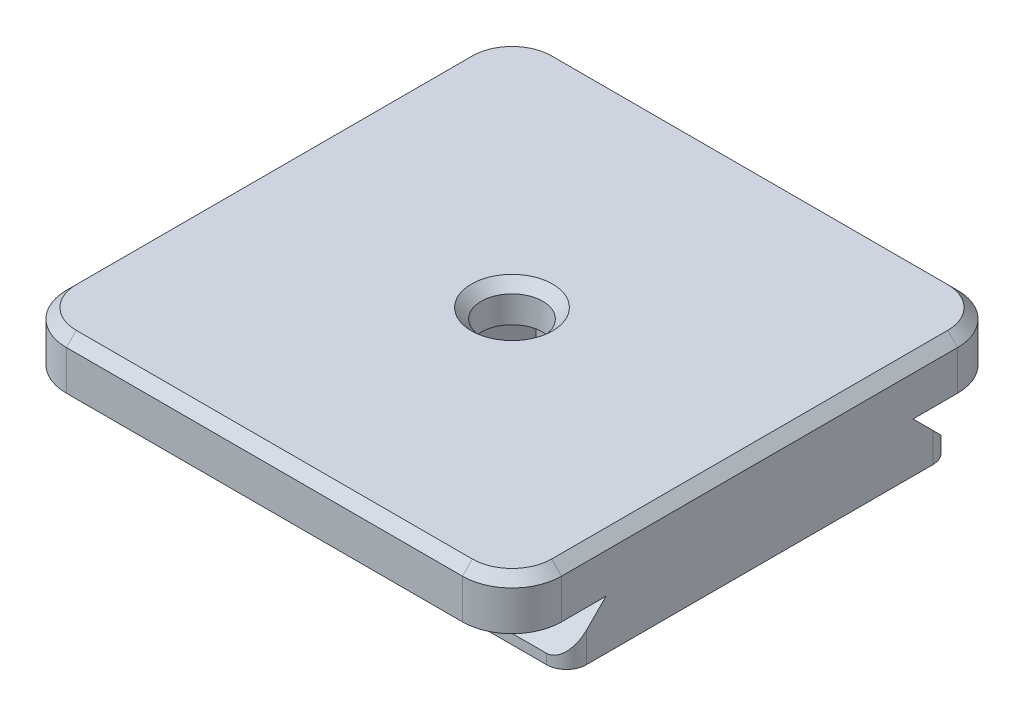
SolidWorks part; units mm, degrees
ref_plane "Front Plane" through (0, 0, 0) normal (0, 0, 1) x (1, 0, 0)
ref_plane "Top Plane" through (0, 0, 0) normal (0, 1, 0) x (1, 0, 0)
ref_plane "Right Plane" through (0, 0, 0) normal (1, 0, 0) x (0, 0, -1)
sketch "Sketch1" plane through (0, 0, 0) normal (0, 1, 0) x (1, 0, 0)
  line L1 (25, -25) -> (-25, -25)
  line L2 (25, -25) -> (25, 25)
  line L3 (25, 25) -> (-25, 25)
  line L4 (-25, -25) -> (-25, 25)
  line L5 (25, -25) -> (-25, 25) construction
  line L6 (25, 25) -> (-25, -25) construction
  point P0 (0, 0)
  dimension "D1" = 50
  dimension "D2" = 50
extrude "Boss-Extrude1" add sketch "Sketch1" along normal blind 10
sketch "Sketch4" plane through (0, 0, 0) normal (0, -1, 0) x (-1, 0, 0)
  line L0 (21, -7.2284) -> (21, -10.5)
  line L1 (-18.5, 13) -> (18.5, 13)
  line L2 (-21, 10.5) -> (-21, 7.2284)
  line L3 (-18.5, -13) -> (18.5, -13)
  line L4 (21, 10.5) -> (21, 7.2284)
  line L5 (-21, 13) -> (21, -13) construction
  line L6 (-21, -13) -> (21, 13) construction
  line L7 (-21, -7.2284) -> (-21, -10.5)
  arc A0 (19.5333, 5.3008) -> (19.5333, -5.3008) centre (21, 0) ccw
  arc A1 (-19.5333, -5.3008) -> (-19.5333, 5.3008) centre (-21, 0) ccw
  arc A2 (-21, -10.5) -> (-18.5, -13) centre (-18.5, -10.5) ccw
  arc A3 (-18.5, 13) -> (-21, 10.5) centre (-18.5, 10.5) ccw
  arc A4 (18.5, 13) -> (21, 10.5) centre (18.5, 10.5) cw
  arc A5 (18.5, -13) -> (21, -10.5) centre (18.5, -10.5) ccw
  arc A6 (-19.5333, -5.3008) -> (-21, -7.2284) centre (-19, -7.2284) ccw
  arc A7 (-21, 7.2284) -> (-19.5333, 5.3008) centre (-19, 7.2284) ccw
  arc A8 (19.5333, 5.3008) -> (21, 7.2284) centre (19, 7.2284) ccw
  arc A9 (19.5333, -5.3008) -> (21, -7.2284) centre (19, -7.2284) cw
  point P0 (0, 0)
  point P26 (-21, -5.5)
  point P33 (21, -5.5)
  dimension "D3" = 11
  dimension "D4" = 11
  dimension "D5" = 2.5
  dimension "D6" = 2
  dimension "D1" = 42
  dimension "D2" = 26
extrude "Cut-Extrude3" cut sketch "Sketch4" against normal blind 6.3
sketch "Sketch5" plane through (0, 6.3, 0) normal (0, -1, 0) x (-1, 0, 0)
  circle A0 centre (0, 0) radius 9
  circle A1 centre (0, 0) radius 3.1
  dimension "D1" = 18
  dimension "D2" = 6.2
extrude "Boss-Extrude2" add sketch "Sketch5" along normal blind 6
sketch "Sketch6" plane through (0, 0, 0) normal (0, -1, 0) x (1, 0, 0)
  line L0 (-25, -25) -> (-25, 25) construction
  circle A0 centre (-20, 0) radius 2.7
  circle A1 centre (20, 0) radius 2.7
  dimension "D1" = 5.4
  dimension "D2" = 40
  dimension "D3" = 5
extrude "Boss-Extrude3" add sketch "Sketch6" along normal blind 2.5
fillet "Fillet1" radius 0.5 2 edges at (20, -2.5, -2.7) (-20, -2.5, -2.7)
sketch "Sketch8" plane through (25, 0, 0) normal (1, 0, 0) x (0, 0, -1)
  line L0 (25, 10) -> (25, 0) construction
  line L16 (-25, 0) -> (-25, 5)
  line L17 (-25, 5) -> (-15.5, 5)
  line L18 (25, 0) -> (25, 5)
  line L19 (15.5, 5) -> (25, 5)
  line L20 (-25, 0) -> (25, 0) construction
  line L22 (-20.5, 0) -> (-15.5, 5)
  line L23 (20.5, 0) -> (15.5, 5)
  line L24 (-20.5, 0) -> (-25, 0)
  line L25 (20.5, 0) -> (25, 0)
  dimension "D1" = 9.5
  dimension "D2" = 45
extrude "Cut-Extrude4" cut sketch "Sketch8" against normal through all
fillet "Fillet2" radius 5 4 edges at (25, 7.5, -25) (-25, 7.5, -25) (-25, 7.5, 25) (25, 7.5, 25)
chamfer "Chamfer1" distance 1 angle 45 8 edges at (23.5355, 10, 23.5355) (0, 10, 25) (-23.5355, 10, 23.5355) (-25, 10, 0) (-23.5355, 10, -23.5355) (0, 10, -25) (23.5355, 10, -23.5355) (25, 10, 0)
chamfer "Chamfer2" distance 1 angle 90 2 edges at (0, 0, 20.5) (0, 0, -20.5)
fillet "Fillet3" radius 2 4 edges at (25, 0.5, -19.5) (25, 0.5, 19.5) (-25, 0.5, 19.5) (-25, 0.5, -19.5)
sketch "Sketch9" plane through (0, 6.3, 0) normal (0, -1, 0) x (-1, 0, 0)
  circle A0 centre (0, 0) radius 3.1
extrude "Cut-Extrude5" cut sketch "Sketch9" against normal through all
chamfer "Chamfer3" distance 1 angle 45 1 edges at (0, 10, -3.1)
sketch "Sketch10" plane through (0, 0.3, 0) normal (0, -1, 0) x (-1, 0, 0)
  line L1 (3.31, -5.7331) -> (6.62, 0)
  line L2 (6.62, 0) -> (3.31, 5.7331)
  line L3 (3.31, 5.7331) -> (-3.31, 5.7331)
  line L4 (-3.31, 5.7331) -> (-6.62, 0)
  line L5 (-6.62, 0) -> (-3.31, -5.7331)
  line L6 (-3.31, -5.7331) -> (3.31, -5.7331)
  circle A0 centre (0, 0) radius 5.7331 construction
  dimension "D1" = 6.62
extrude "Cut-Extrude6" cut sketch "Sketch10" against normal blind 6
fillet "Fillet4" radius 3 1 edges at (0, 6.3, -9)
